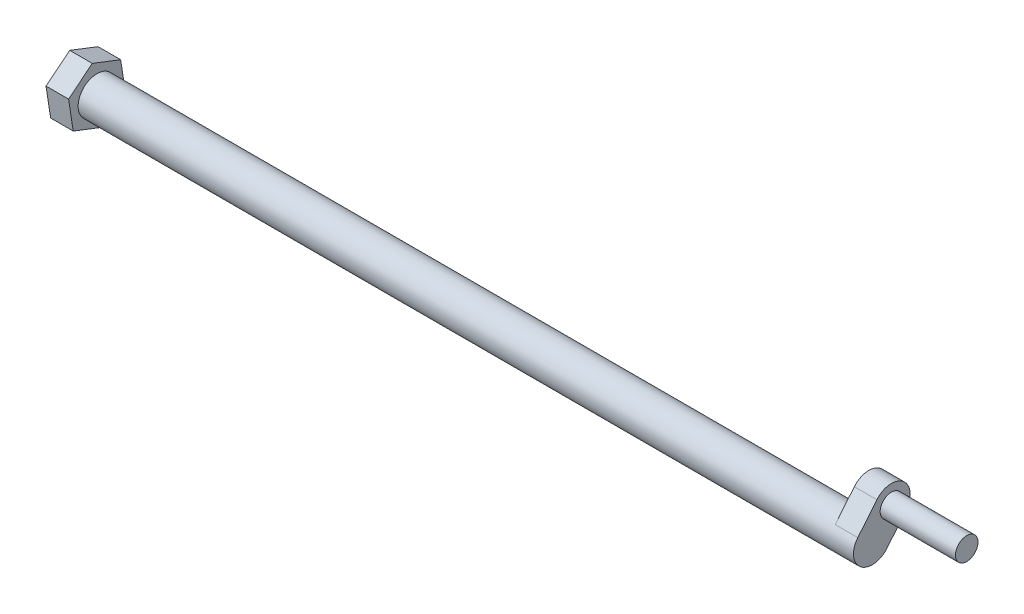
SolidWorks part; units mm, degrees
ref_plane "前基準面" through (0, 0, 0) normal (0, 0, 1) x (1, 0, 0)
ref_plane "上基準面" through (0, 0, 0) normal (0, 1, 0) x (1, 0, 0)
ref_plane "右基準面" through (0, 0, 0) normal (1, 0, 0) x (0, 0, -1)
sketch "草圖1" plane through (0, 0, 0) normal (1, 0, 0) x (0, 0, -1)
  circle A0 centre (0, 0) radius 2.5
  dimension "D1" = 5
extrude "填料-伸長1" add sketch "草圖1" along normal blind 100
sketch "草圖2" plane through (100, 0, 0) normal (1, 0, 0) x (0, 0, -1)
  line L0 (0, 0) -> (2.5407, 3.0895) construction
  line L1 (-1.9309, 1.5879) -> (0.6097, 4.6774)
  line L2 (1.9309, -1.5879) -> (4.4716, 1.5016)
  arc A1 (-1.9309, 1.5879) -> (1.9309, -1.5879) centre (0, 0) ccw
  arc A2 (4.4716, 1.5016) -> (0.6097, 4.6774) centre (2.5407, 3.0895) ccw
  point P5 (1.2703, 1.5448)
  dimension "D1" = 2.5
  dimension "D2" = 4
extrude "填料-伸長2" add sketch "草圖2" along normal blind 3
sketch "草圖3" plane through (103, 0, 0) normal (1, 0, 0) x (0, 0, -1)
  circle A0 centre (2.5407, 3.0895) radius 1.5
  dimension "D1" = 3
extrude "填料-伸長3" add sketch "草圖3" along normal blind 10
sketch "草圖4" plane through (0, 0, 0) normal (1, 0, 0) x (0, 0, -1)
  line L1 (-3.149, -2.5332) -> (0.6193, -3.9937)
  line L2 (0.6193, -3.9937) -> (3.7683, -1.4606)
  line L3 (3.7683, -1.4606) -> (3.149, 2.5332)
  line L4 (3.149, 2.5332) -> (-0.6193, 3.9937)
  line L5 (-0.6193, 3.9937) -> (-3.7683, 1.4606)
  line L6 (-3.7683, 1.4606) -> (-3.149, -2.5332)
  circle A0 centre (0, 0) radius 3.5 construction
  dimension "D1" = 7
extrude "填料-伸長4" add sketch "草圖4" against normal blind 3
